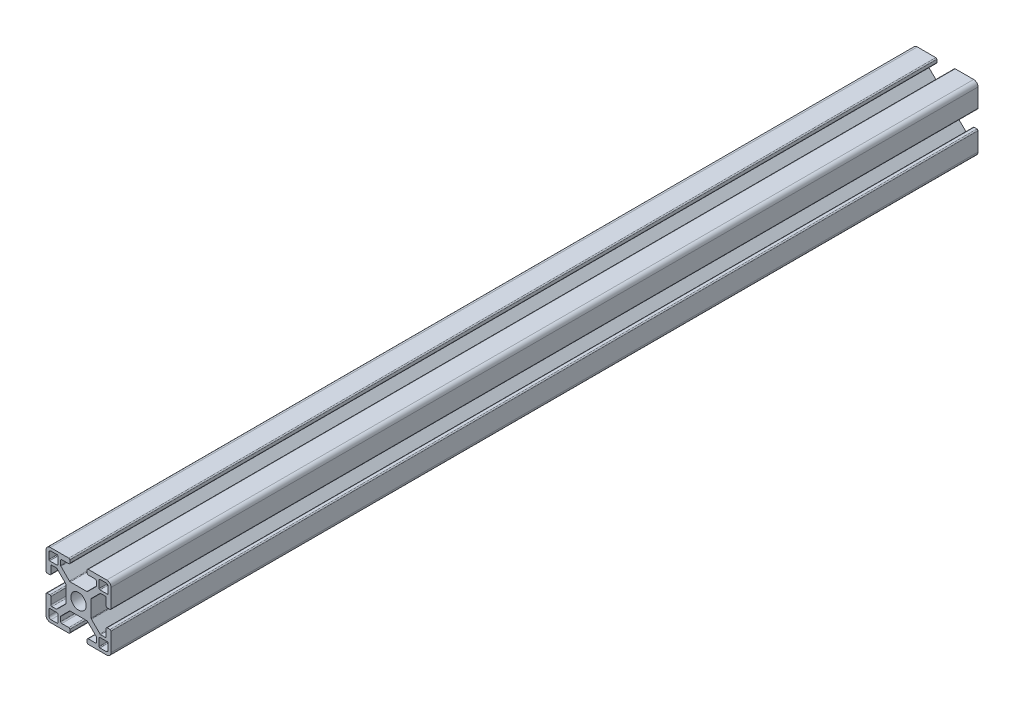
SolidWorks part; units mm, degrees
ref_plane "Front Plane" through (0, 0, 0) normal (0, 0, 1) x (1, 0, 0)
ref_plane "Top Plane" through (0, 0, 0) normal (0, 1, 0) x (1, 0, 0)
ref_plane "Right Plane" through (0, 0, 0) normal (1, 0, 0) x (0, 0, -1)
sketch "Sketch1" plane through (0, 0, 0) normal (0, 0, 1) x (1, 0, 0)
  line L0 (3.9799, -2.4733) -> (3.1981, -1.4942) construction
  line L1 (1.4942, -3.1981) -> (2.4733, -3.9799) construction
  line L2 (-2.4733, -3.9799) -> (-1.4942, -3.1981) construction
  line L3 (-3.1981, -1.4942) -> (-3.9799, -2.4733) construction
  line L4 (-3.9799, 2.4733) -> (-3.1981, 1.4942) construction
  line L5 (-1.4942, 3.1981) -> (-2.4733, 3.9799) construction
  line L6 (2.4733, 3.9799) -> (1.4942, 3.1981) construction
  line L7 (3.1981, 1.4942) -> (3.9799, 2.4733) construction
  line L8 (-12.6999, -13.6999) -> (-9.881, -13.6999)
  line L9 (-13.6999, -9.881) -> (-13.6999, -12.6999)
  line L10 (-9.88, -9.5) -> (-13.3189, -9.5)
  line L11 (-9.5, -13.3189) -> (-9.5, -9.88)
  line L12 (13.6999, -12.6999) -> (13.6999, -9.881)
  line L13 (9.881, -13.6999) -> (12.6999, -13.6999)
  line L14 (9.5, -9.88) -> (9.5, -13.3189)
  line L15 (13.3189, -9.5) -> (9.88, -9.5)
  line L16 (9.88, 9.5) -> (13.3189, 9.5)
  line L17 (9.5, 13.3189) -> (9.5, 9.88)
  line L18 (12.6999, 13.6999) -> (9.881, 13.6999)
  line L19 (13.6999, 9.881) -> (13.6999, 12.6999)
  line L20 (-13.6999, 12.6999) -> (-13.6999, 9.881)
  line L21 (-9.881, 13.6999) -> (-12.6999, 13.6999)
  line L22 (-9.5, 9.88) -> (-9.5, 13.3189)
  line L23 (-13.3189, 9.5) -> (-9.88, 9.5)
  line L24 (14.4999, -4) -> (13.2425, -4)
  line L25 (12.7425, -4.5) -> (12.7425, -7.7325)
  line L26 (12.2428, -8.25) -> (10.2602, -8.25)
  line L27 (9.9066, -8.1035) -> (5.9811, -4.178)
  line L28 (5.8347, -3.8245) -> (5.8347, -1.0125)
  line L29 (5.8347, -1.0125) -> (5.3247, -0.0625) construction
  line L30 (5.3247, -0.0625) -> (5.8347, 0.8875) construction
  line L31 (5.8347, 0.8875) -> (5.8347, 3.8245)
  line L32 (5.9811, 4.178) -> (9.9066, 8.1035)
  line L33 (10.2602, 8.25) -> (12.2428, 8.25)
  line L34 (12.7425, 7.7325) -> (12.7425, 4.5)
  line L35 (13.2425, 4) -> (14.4999, 4)
  line L36 (14.9999, 4.5) -> (14.9999, 12.9999)
  line L37 (12.9999, 14.9999) -> (4.5, 14.9999)
  line L38 (4, 14.4999) -> (4, 13.2425)
  line L39 (4.5, 12.7425) -> (7.7325, 12.7425)
  line L40 (8.25, 12.2428) -> (8.25, 10.2602)
  line L41 (8.1035, 9.9066) -> (4.178, 5.9811)
  line L42 (3.8245, 5.8347) -> (0.95, 5.8347)
  line L43 (0.95, 5.8347) -> (0, 5.3247) construction
  line L44 (0, 5.3247) -> (-0.95, 5.8347) construction
  line L45 (-0.95, 5.8347) -> (-3.8245, 5.8347)
  line L46 (-4.178, 5.9811) -> (-8.1035, 9.9066)
  line L47 (-8.25, 10.2602) -> (-8.25, 12.2428)
  line L48 (-7.7325, 12.7425) -> (-4.5, 12.7425)
  line L49 (-4, 13.2425) -> (-4, 14.4999)
  line L50 (-4.5, 14.9999) -> (-12.9999, 14.9999)
  line L51 (-14.9999, 12.9999) -> (-14.9999, 4.5)
  line L52 (-14.4999, 4) -> (-13.2425, 4)
  line L53 (-12.7425, 4.5) -> (-12.7425, 7.7325)
  line L54 (-12.2428, 8.25) -> (-10.2602, 8.25)
  line L55 (-9.9066, 8.1035) -> (-5.9811, 4.178)
  line L56 (-5.8347, 3.8245) -> (-5.8347, 0.8875)
  line L57 (-5.8347, 0.8875) -> (-5.3247, -0.0625) construction
  line L58 (-5.3247, -0.0625) -> (-5.8347, -1.0125) construction
  line L59 (-5.8347, -1.0125) -> (-5.8347, -3.8245)
  line L60 (-5.9811, -4.178) -> (-9.9066, -8.1035)
  line L61 (-10.2602, -8.25) -> (-12.2428, -8.25)
  line L62 (-12.7425, -7.7325) -> (-12.7425, -4.5)
  line L63 (-13.2425, -4) -> (-14.4999, -4)
  line L64 (-14.9999, -4.5) -> (-14.9999, -12.9999)
  line L65 (-12.9999, -14.9999) -> (-4.5, -14.9999)
  line L66 (-4, -14.4999) -> (-4, -13.2425)
  line L67 (-4.5, -12.7425) -> (-7.7325, -12.7425)
  line L68 (-8.25, -12.2428) -> (-8.25, -10.2602)
  line L69 (-8.1035, -9.9066) -> (-4.178, -5.9811)
  line L70 (-3.8245, -5.8347) -> (-0.95, -5.8347)
  line L71 (-0.95, -5.8347) -> (0, -5.3247) construction
  line L72 (0, -5.3247) -> (0.95, -5.8347) construction
  line L73 (0.95, -5.8347) -> (3.8245, -5.8347)
  line L74 (4.178, -5.9811) -> (8.1035, -9.9066)
  line L75 (8.25, -10.2602) -> (8.25, -12.2428)
  line L76 (7.7325, -12.7425) -> (4.5, -12.7425)
  line L77 (4, -13.2425) -> (4, -14.4999)
  line L78 (4.5, -14.9999) -> (12.9999, -14.9999)
  line L79 (14.9999, -12.9999) -> (14.9999, -4.5)
  line L80 (-5.8347, -1.0125) -> (-5.8347, 0.8875)
  line L81 (-0.95, 5.8347) -> (0.95, 5.8347)
  line L82 (5.8347, 0.8875) -> (5.8347, -1.0125)
  line L83 (-0.95, -5.8347) -> (0.95, -5.8347)
  arc A0 (2.4733, -3.9799) -> (3.9799, -2.4733) centre (3.1422, -3.1422) ccw construction
  arc A1 (-1.4942, -3.1981) -> (1.4942, -3.1981) centre (0, 0) ccw construction
  arc A2 (-3.9799, -2.4733) -> (-2.4733, -3.9799) centre (-3.1422, -3.1422) ccw construction
  arc A3 (-3.1981, 1.4942) -> (-3.1981, -1.4942) centre (0, 0) ccw construction
  arc A4 (-2.4733, 3.9799) -> (-3.9799, 2.4733) centre (-3.1422, 3.1422) ccw construction
  arc A5 (1.4942, 3.1981) -> (-1.4942, 3.1981) centre (0, 0) ccw construction
  arc A6 (3.9799, 2.4733) -> (2.4733, 3.9799) centre (3.1422, 3.1422) ccw construction
  arc A7 (3.1981, -1.4942) -> (3.1981, 1.4942) centre (0, 0) ccw construction
  arc A8 (-13.6999, -12.6999) -> (-12.6999, -13.6999) centre (-12.6999, -12.6999) ccw
  arc A9 (-13.3189, -9.5) -> (-13.6999, -9.881) centre (-13.3189, -9.881) ccw
  arc A10 (-9.5, -9.88) -> (-9.88, -9.5) centre (-9.88, -9.88) ccw
  arc A11 (-9.881, -13.6999) -> (-9.5, -13.3189) centre (-9.881, -13.3189) ccw
  arc A12 (12.6999, -13.6999) -> (13.6999, -12.6999) centre (12.6999, -12.6999) ccw
  arc A13 (9.5, -13.3189) -> (9.881, -13.6999) centre (9.881, -13.3189) ccw
  arc A14 (9.88, -9.5) -> (9.5, -9.88) centre (9.88, -9.88) ccw
  arc A15 (13.6999, -9.881) -> (13.3189, -9.5) centre (13.3189, -9.881) ccw
  arc A16 (9.5, 9.88) -> (9.88, 9.5) centre (9.88, 9.88) ccw
  arc A17 (9.881, 13.6999) -> (9.5, 13.3189) centre (9.881, 13.3189) ccw
  arc A18 (13.6999, 12.6999) -> (12.6999, 13.6999) centre (12.6999, 12.6999) ccw
  arc A19 (13.3189, 9.5) -> (13.6999, 9.881) centre (13.3189, 9.881) ccw
  arc A20 (14.9999, -4.5) -> (14.4999, -4) centre (14.4999, -4.5) ccw
  arc A21 (13.2425, -4) -> (12.7425, -4.5) centre (13.2425, -4.5) ccw
  arc A22 (12.2428, -8.25) -> (12.7425, -7.7325) centre (12.2428, -7.75) ccw
  arc A23 (9.9066, -8.1035) -> (10.2602, -8.25) centre (10.2602, -7.75) ccw
  arc A24 (5.8347, -3.8245) -> (5.9811, -4.178) centre (6.3347, -3.8245) ccw
  arc A25 (5.9811, 4.178) -> (5.8347, 3.8245) centre (6.3347, 3.8245) ccw
  arc A26 (10.2602, 8.25) -> (9.9066, 8.1035) centre (10.2602, 7.75) ccw
  arc A27 (12.7425, 7.7325) -> (12.2428, 8.25) centre (12.2428, 7.75) ccw
  arc A28 (12.7425, 4.5) -> (13.2425, 4) centre (13.2425, 4.5) ccw
  arc A29 (14.4999, 4) -> (14.9999, 4.5) centre (14.4999, 4.5) ccw
  arc A30 (14.9999, 12.9999) -> (12.9999, 14.9999) centre (12.9999, 12.9999) ccw
  arc A31 (4.5, 14.9999) -> (4, 14.4999) centre (4.5, 14.4999) ccw
  arc A32 (4, 13.2425) -> (4.5, 12.7425) centre (4.5, 13.2425) ccw
  arc A33 (8.25, 12.2428) -> (7.7325, 12.7425) centre (7.75, 12.2428) ccw
  arc A34 (8.1035, 9.9066) -> (8.25, 10.2602) centre (7.75, 10.2602) ccw
  arc A35 (3.8245, 5.8347) -> (4.178, 5.9811) centre (3.8245, 6.3347) ccw
  arc A36 (-4.178, 5.9811) -> (-3.8245, 5.8347) centre (-3.8245, 6.3347) ccw
  arc A37 (-8.25, 10.2602) -> (-8.1035, 9.9066) centre (-7.75, 10.2602) ccw
  arc A38 (-7.7325, 12.7425) -> (-8.25, 12.2428) centre (-7.75, 12.2428) ccw
  arc A39 (-4.5, 12.7425) -> (-4, 13.2425) centre (-4.5, 13.2425) ccw
  arc A40 (-4, 14.4999) -> (-4.5, 14.9999) centre (-4.5, 14.4999) ccw
  arc A41 (-12.9999, 14.9999) -> (-14.9999, 12.9999) centre (-12.9999, 12.9999) ccw
  arc A42 (-14.9999, 4.5) -> (-14.4999, 4) centre (-14.4999, 4.5) ccw
  arc A43 (-13.2425, 4) -> (-12.7425, 4.5) centre (-13.2425, 4.5) ccw
  arc A44 (-12.2428, 8.25) -> (-12.7425, 7.7325) centre (-12.2428, 7.75) ccw
  arc A45 (-9.9066, 8.1035) -> (-10.2602, 8.25) centre (-10.2602, 7.75) ccw
  arc A46 (-5.8347, 3.8245) -> (-5.9811, 4.178) centre (-6.3347, 3.8245) ccw
  arc A47 (-5.9811, -4.178) -> (-5.8347, -3.8245) centre (-6.3347, -3.8245) ccw
  arc A48 (-10.2602, -8.25) -> (-9.9066, -8.1035) centre (-10.2602, -7.75) ccw
  arc A49 (-12.7425, -7.7325) -> (-12.2428, -8.25) centre (-12.2428, -7.75) ccw
  arc A50 (-12.7425, -4.5) -> (-13.2425, -4) centre (-13.2425, -4.5) ccw
  arc A51 (-14.4999, -4) -> (-14.9999, -4.5) centre (-14.4999, -4.5) ccw
  arc A52 (-14.9999, -12.9999) -> (-12.9999, -14.9999) centre (-12.9999, -12.9999) ccw
  arc A53 (-4.5, -14.9999) -> (-4, -14.4999) centre (-4.5, -14.4999) ccw
  arc A54 (-4, -13.2425) -> (-4.5, -12.7425) centre (-4.5, -13.2425) ccw
  arc A55 (-8.25, -12.2428) -> (-7.7325, -12.7425) centre (-7.75, -12.2428) ccw
  arc A56 (-8.1035, -9.9066) -> (-8.25, -10.2602) centre (-7.75, -10.2602) ccw
  arc A57 (-3.8245, -5.8347) -> (-4.178, -5.9811) centre (-3.8245, -6.3347) ccw
  arc A58 (4.178, -5.9811) -> (3.8245, -5.8347) centre (3.8245, -6.3347) ccw
  arc A59 (8.25, -10.2602) -> (8.1035, -9.9066) centre (7.75, -10.2602) ccw
  arc A60 (7.7325, -12.7425) -> (8.25, -12.2428) centre (7.75, -12.2428) ccw
  arc A61 (4.5, -12.7425) -> (4, -13.2425) centre (4.5, -13.2425) ccw
  arc A62 (4, -14.4999) -> (4.5, -14.9999) centre (4.5, -14.4999) ccw
  arc A63 (12.9999, -14.9999) -> (14.9999, -12.9999) centre (12.9999, -12.9999) ccw
  arc A64 (-12.6999, 13.6999) -> (-13.6999, 12.6999) centre (-12.6999, 12.6999) ccw
  arc A65 (-9.5, 13.3189) -> (-9.881, 13.6999) centre (-9.881, 13.3189) ccw
  arc A66 (-9.88, 9.5) -> (-9.5, 9.88) centre (-9.88, 9.88) ccw
  arc A67 (-13.6999, 9.881) -> (-13.3189, 9.5) centre (-13.3189, 9.881) ccw
  circle A68 centre (0, 0) radius 3.53
extrude "Boss-Extrude1" add sketch "Sketch1" along normal mid plane 400
